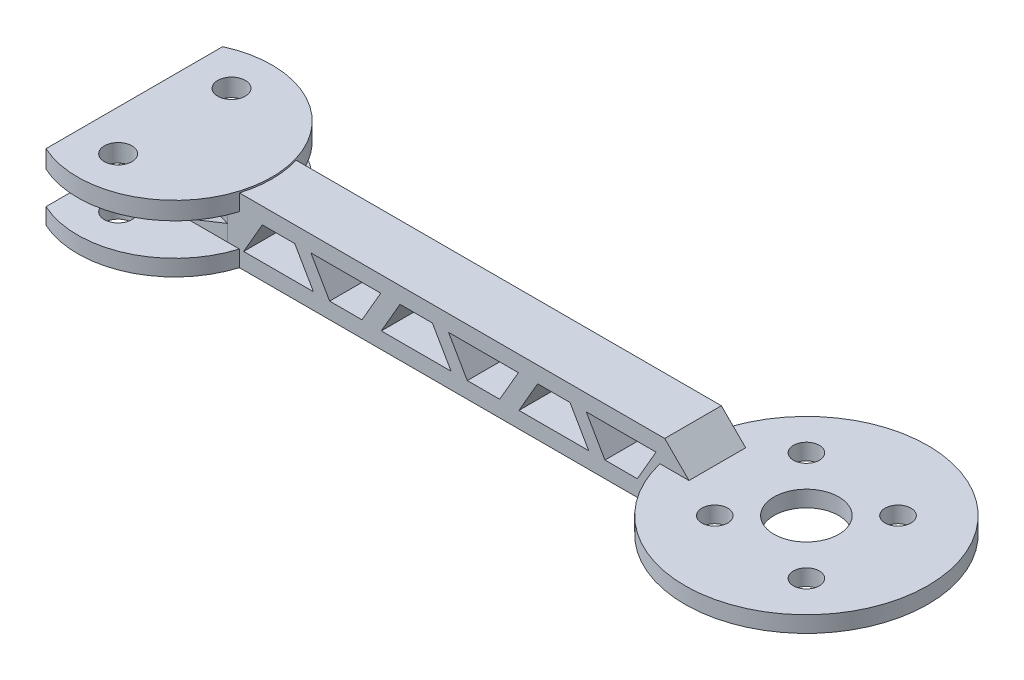
SolidWorks part; units mm, degrees
material "Thornel Mat VMA"
ref_plane "前视基准面" through (0, 0, 0) normal (0, 0, 1) x (1, 0, 0)
ref_plane "上视基准面" through (0, 0, 0) normal (0, 1, 0) x (1, 0, 0)
ref_plane "右视基准面" through (0, 0, 0) normal (1, 0, 0) x (0, 0, -1)
other "Configuration Table"
sketch "草图1" plane through (0, 0, 0) normal (0, 1, 0) x (1, 0, 0)
  line L0 (0, -3.5) -> (54.25, -3.5)
  line L1 (54.25, -3.5) -> (54.25, 3.5)
  line L2 (54.25, 3.5) -> (0, 3.5)
  line L3 (0, 3.5) -> (0, -3.5)
  dimension "D1" = 3.5
  dimension "D2" = 3.5
extrude "凸台-拉伸1" add sketch "草图1" along normal blind 2
sketch "草图2" plane through (0, 0, 0) normal (0, 1, 0) x (1, 0, 0)
  circle A0 centre (0, 0) radius 12
  circle A1 centre (0, -7) radius 1.7
  circle A2 centre (0, 7) radius 1.7
extrude "凸台-拉伸2" add sketch "草图2" along normal blind 2
sketch "草图3" plane through (0, 0, 0) normal (0, 1, 0) x (1, 0, 0)
  circle A0 centre (0, 0) radius 12
  circle A1 centre (0, -7) radius 1.7
  circle A2 centre (0, 7) radius 1.7
  dimension "D1" = 24
extrude "凸台-拉伸3" add sketch "草图3" along normal blind 2.2 from offset 6
ref_plane "基准面1" through (0, 4, 0) normal (0, -1, 0) x (-1, 0, 0)
sketch "草图5" plane through (0, 4, 0) normal (0, 1, 0) x (1, 0, 0)
  line L0 (78, 0) -> (104.6124, 0) construction
  line L1 (78, 0) -> (78, 21.049) construction
  line L2 (72.3431, -5.6569) -> (83.6569, 5.6569) construction
  line L3 (71.2825, 6.7175) -> (84.7175, -6.7175) construction
  line L4 (78, 0) -> (59.4412, 18.5588) construction
  circle A0 centre (78, 0) radius 15
  circle A1 centre (72.3431, -5.6569) radius 1.6
  circle A2 centre (71.2825, 6.7175) radius 1.6
  circle A3 centre (84.7175, -6.7175) radius 1.6
  circle A4 centre (83.6569, 5.6569) radius 1.6
  circle A5 centre (78, 0) radius 4
  dimension "D5" = 3.2
  dimension "D6" = 8
  dimension "D1" = 45
  dimension "D2" = 8
  dimension "D3" = 78
  dimension "D4" = 9.5
extrude "凸台-拉伸5" add sketch "草图5" along normal blind 1 and the other way blind 1
sketch "草图4" plane through (0, 0, 0) normal (0, 1, 0) x (1, 0, 0)
  line L0 (-10, -3.5) -> (10, -3.5)
  line L1 (10, -3.5) -> (10, 3.5)
  line L2 (10, 3.5) -> (-10, 3.5)
  line L3 (-10, 3.5) -> (-10, -3.5)
  dimension "D1" = 3.5
  dimension "D2" = 3.5
  dimension "D3" = 10
sketch "草图6" plane through (0, 0, 0) normal (0, 0, 1) x (1, 0, 0)
  line L0 (10, 0) -> (64, 0)
  line L1 (67, 3) -> (67, 5)
  line L2 (64, 8) -> (10, 8)
  line L3 (31.3094, 6) -> (29, 2)
  line L5 (12, 2) -> (20.6188, 2)
  line L6 (11.4782, 2) -> (-12, 2) construction
  line L7 (11.4782, 2) -> (54.25, 2) construction
  line L8 (20.6188, 2) -> (18.3094, 6)
  line L9 (18.3094, 6) -> (14.3094, 6)
  line L10 (29, 2) -> (37.6188, 2)
  line L11 (14.3094, 6) -> (12, 2)
  line L12 (20.3094, 6) -> (28.9282, 6)
  line L13 (28.9282, 6) -> (26.6188, 2)
  line L14 (26.6188, 2) -> (22.6188, 2)
  line L15 (22.6188, 2) -> (20.3094, 6)
  line L25 (37.6188, 2) -> (35.3094, 6)
  line L29 (-10, 0) -> (10, 0) construction
  line L30 (10, 8) -> (10, 0)
  line L31 (39.6188, 2) -> (37.3094, 6)
  line L32 (37.3094, 6) -> (45.9282, 6)
  line L33 (45.9282, 6) -> (43.6188, 2)
  line L34 (43.6188, 2) -> (39.6188, 2)
  line L35 (35.3094, 6) -> (31.3094, 6)
  line L36 (48.3094, 6) -> (46, 2)
  line L37 (46, 2) -> (54.6188, 2)
  line L38 (54.6188, 2) -> (52.3094, 6)
  line L39 (56.6188, 2) -> (54.3094, 6)
  line L40 (54.3094, 6) -> (62.9282, 6)
  line L41 (62.9282, 6) -> (60.6188, 2)
  line L42 (60.6188, 2) -> (56.6188, 2)
  line L43 (52.3094, 6) -> (48.3094, 6)
  line L52 (73.6188, 2) -> (71.3094, 6) [skipped]
  line L53 (71.3094, 6) -> (79.9282, 6) [skipped]
  line L54 (79.9282, 6) -> (77.6188, 2) [skipped]
  line L55 (77.6188, 2) -> (73.6188, 2) [skipped]
  line L56 (14.3094, 6) -> (31.3094, 6) construction
  line L57 (71.6188, 2) -> (69.3094, 6) [skipped]
  line L58 (65.3094, 6) -> (63, 2) [skipped]
  line L59 (63, 2) -> (71.6188, 2) [skipped]
  line L60 (69.3094, 6) -> (65.3094, 6) [skipped]
  line L61 (67, 5) -> (64, 8)
  line L62 (93, 5) -> (63, 5) construction
  line L63 (67, 3) -> (64, 0)
  line L64 (63, 3) -> (93, 3) construction
  dimension "D1" = 8
  dimension "D2" = 6
  dimension "D3" = 10
  dimension "D4" = 4
  dimension "D5" = 4
  dimension "D6" = 60
  dimension "D7" = 60
  dimension "D8" = 60
  dimension "D9" = 60
  dimension "D11" = 2
  dimension "D12" = 17
  dimension "D13" = 12
  dimension "D14" = 67
  dimension "D15" = 135
  dimension "D16" = 135
  dimension "D10" = 4
extrude "凸台-拉伸6" add sketch "草图6" along normal blind 7 from offset 3.5
other "角撑板1" parameters "D1"=7, "D2"=7, "D3"=0, "D4"=0, "D10"=5, "D11"=2, "D12"=5, "D13"=15, "D14"=45, "D15"=15
sketch "草图7" plane through (10, 6, 0) normal (0, 0, -1) x (-1, 0, 0)
  line L0 (0, 0) -> (0, -2)
  line L1 (0, 0) -> (5, 0)
  line L2 (0, -2) -> (5, 0)
other "角撑板2" parameters "D1"=7, "D2"=7, "D3"=0, "D4"=0, "D10"=5, "D11"=2, "D12"=5, "D13"=15, "D14"=45, "D15"=15
sketch "草图8" plane through (10, 2, 0) normal (0, 0, 1) x (1, 0, 0)
  line L0 (0, 0) -> (0, 2)
  line L1 (0, 0) -> (-5, 0)
  line L2 (0, 2) -> (-5, 0)
sketch "草图9" plane through (0, 4, 0) normal (0, -1, 0) x (-1, 0, 0)
  line L0 (0, 0) -> (26.6225, 0) construction
  line L1 (0, 0) -> (0, -19.9472) construction
  line L2 (5, 12.2193) -> (5, -12.2193)
  line L3 (5, 12.2193) -> (15, 12.2193)
  line L4 (15, 12.2193) -> (15, -12.2193)
  line L5 (5, -12.2193) -> (15, -12.2193)
  point P13 (15, 0)
  point P14 (5, 0)
  dimension "D1" = 5
  dimension "D2" = 10
extrude "切除-拉伸1" cut sketch "草图9" against normal blind 10 and the other way blind 10
